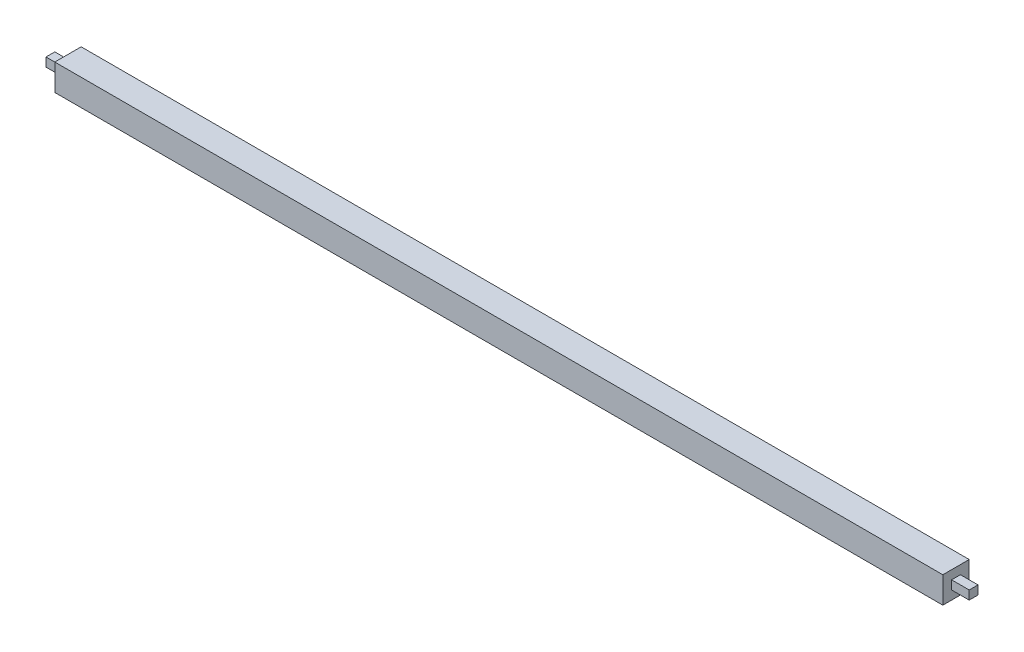
SolidWorks part; units mm, degrees
ref_plane "Přední rovina" through (0, 0, 0) normal (0, 0, 1) x (1, 0, 0)
ref_plane "Horní rovina" through (0, 0, 0) normal (0, 1, 0) x (1, 0, 0)
ref_plane "Pravá rovina" through (0, 0, 0) normal (1, 0, 0) x (0, 0, -1)
sketch "Skica1" plane through (0, 0, 0) normal (0, 1, 0) x (1, 0, 0)
  line L0 (0, 0) -> (202, 0)
  line L1 (202, 0) -> (202, 6)
  line L2 (202, 6) -> (0, 6)
  line L3 (0, 6) -> (0, 0)
  dimension "D1" = 6
  dimension "D2" = 202
extrude "Přidat vysunutím1" add sketch "Skica1" along normal blind 6
sketch "Skica2" plane through (0, 0, 0) normal (-1, 0, 0) x (0, 0, 1)
  line L0 (0, 6) -> (0, 0) construction
  line L1 (-4, 4) -> (-2, 4)
  line L2 (-4, 4) -> (-4, 2)
  line L3 (-4, 2) -> (-2, 2)
  line L4 (-2, 4) -> (-2, 2)
  line L5 (-6, 6) -> (0, 6) construction
  dimension "D1" = 2
  dimension "D2" = 2
  dimension "D3" = 2
  dimension "D4" = 2
extrude "Přidat vysunutím2" add sketch "Skica2" along normal blind 4
sketch "Skica3" plane through (202, 0, 0) normal (1, 0, 0) x (0, 0, -1)
  line L0 (6, 6) -> (6, 0) construction
  line L1 (2, 4) -> (4, 4)
  line L2 (2, 4) -> (2, 2)
  line L3 (2, 2) -> (4, 2)
  line L4 (4, 4) -> (4, 2)
  line L6 (0, 6) -> (6, 6) construction
  dimension "D1" = 2
  dimension "D2" = 2
  dimension "D3" = 2
  dimension "D4" = 2
extrude "Přidat vysunutím3" add sketch "Skica3" along normal blind 4
